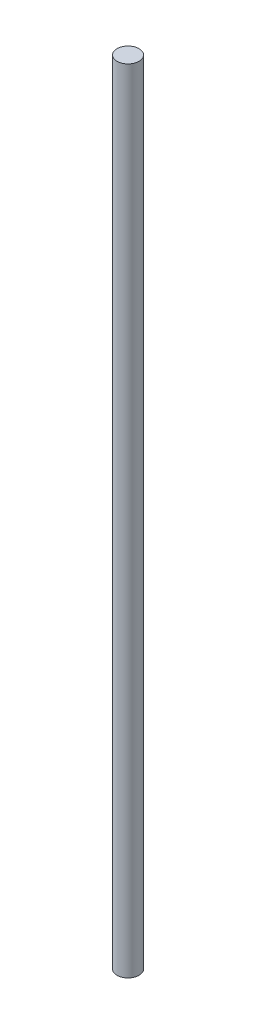
SolidWorks part; units mm, degrees
ref_plane "Спереди" through (0, 0, 0) normal (0, 0, 1) x (1, 0, 0)
ref_plane "Сверху" through (0, 0, 0) normal (0, 1, 0) x (1, 0, 0)
ref_plane "Справа" through (0, 0, 0) normal (1, 0, 0) x (0, 0, -1)
sketch "Эскиз1" plane through (0, 0, 0) normal (0, 1, 0) x (1, 0, 0)
  circle A0 centre (0, 0) radius 2.5
  dimension "D1" = 5
extrude "Бобышка-Вытянуть1" add sketch "Эскиз1" along normal blind 180
equation "\"motor_diameter\"= 30"
equation "\"mm_diameter\"= IIF ( \"motor_diameter\" < 34 , 41 , \"motor_diameter\" + 8 )"
equation "\"upper_shafts_diameter\"= 5"
equation "\"upper_shats_length\"= 180"
equation "\"upper_bearing_d1\"= 10"
equation "\"upper_bearing_d2\"= 5"
equation "\"upper_bearing_h\"= 15"
equation "\"lower_shafts_diameter\"= 5"
equation "\"lower_shafts_length\"= 180"
equation "\"lower_bearing_d1\"= 10"
equation "\"lower_bearing_d2\"= 5"
equation "\"lower_bearing_h\"= 15"
equation "\"print_offset\"= 0.2"
equation "\"bh_screws_d\"= 2"
equation "\"bh_screws_h\"= 20"
equation "\"bh_screws_hh_d\"= 3.4"
equation "\"bh_screws_hh_h\"= 2"
equation "\"bh_nut_d\"= 3.8"
equation "\"bh_nut_h\"= 2"
equation "\"motor_screws_d\"= 3"
equation "\"motor_screws_h\"= 16"
equation "\"motor_screws_hh_d\"= 5.5"
equation "\"motor_screws_hh_h\"= 3"
equation "\"plate_hole_distance\"= 25.4"
equation "\"plate_screws_d\"= 6.5"
equation "\"D1@Эскиз1\"=\"lower_shafts_diameter\""
equation "\"D1@Бобышка-Вытянуть1\"=\"lower_shafts_length\""
